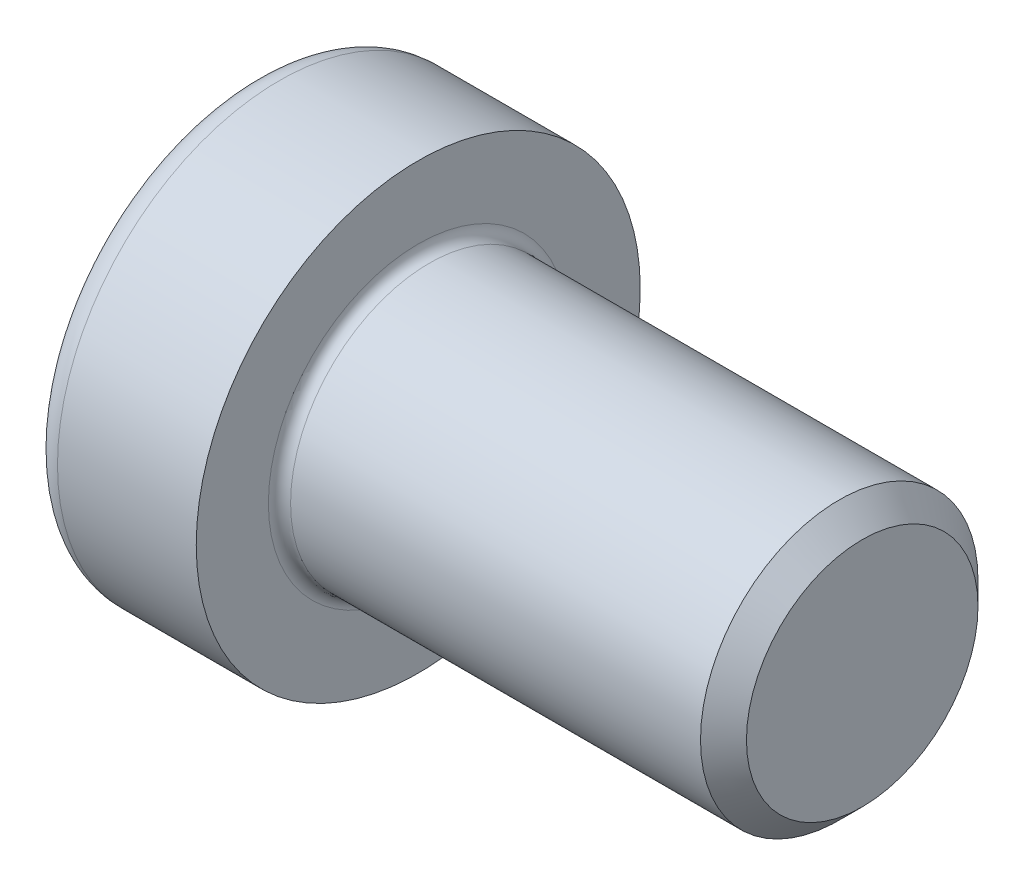
SolidWorks part; units mm, degrees
revolve "Base-Revolve" add sketch "BodySke"
sketch "BodySke" plane through (0, 0, 0) normal (0, 0, 1) x (1, 0, 0)
  line L0 (0, 0) -> (0, 8)
  line L1 (0, 8) -> (6, 8)
  line L2 (6, 8) -> (6, 5)
  line L3 (6, 5) -> (21.172, 5)
  line L4 (22, 4.172) -> (22, 0)
  line L5 (22, 0) -> (0, 0)
  line L6 (-31.75, 0) -> (127, 0) construction
  line L8 (22, 4.172) -> (21.172, 5)
  line L10 (22, -4.172) -> (21.172, -5) construction
  line L11 (7.5, 4.525) -> (7.5, -1.825) construction
  line L12 (10.5, 4.525) -> (10.5, -1.825) construction
  line L13 (-38, 4.525) -> (-38, -1.825) construction
  dimension "Head_ht" = 6
  dimension "Length" = 16
  dimension "Body_ch_ang" = 45
  dimension "Diameter" = 10
  dimension "Minor_dia" = 8.344
  dimension "Advance" = 1.5
  dimension "Thread_nom" = 11.5
  dimension "Thread_length" = 60
  dimension "Head_dia" = 16
cosmetic thread "ThreadCosmetic"
fillet "Fillet1" radius 0.4 1 edges at (6, 0, 5)
fillet "Fillet2" radius 1 1 edges at (0, 0, 8)
material "AISI 316 Нержавеющая сталь, лист (SS)"
ref_plane "Plane1" through (0, 0, 0) normal (0, 0, 1) x (1, 0, 0)
ref_plane "Plane2" through (0, 0, 0) normal (0, 1, 0) x (1, 0, 0)
ref_plane "Plane3" through (0, 0, 0) normal (1, 0, 0) x (0, 0, -1)
other "Configuration Table"
sketch "Sketch2" plane through (0, 0, 0) normal (0, 0, 1) x (1, 0, 0)
  line L0 (0, 3.5) -> (4.5, 3.5)
  line L1 (4.5, 3.5) -> (6.5207, 0)
  line L2 (-31.75, 0) -> (127, 0) construction
  line L3 (6.5207, 0) -> (0, 0)
  line L4 (0, 0) -> (0, 3.5)
  line L6 (0, 0) -> (47.625, 0) construction
  dimension "D1" = 3.5
  dimension "D2" = 60
  dimension "Depth" = 4.5
revolve "Hex-PreBroach" cut sketch "Sketch2" angle 360 about L6
sketch "Sketch3" plane through (0, 0, 0) normal (-1, 0, 0) x (0, 0.5, 0.866)
  line L0 (2.0207, 3.5) -> (-2.0207, 3.5)
  line L1 (-2.0207, 3.5) -> (-4.0415, 0)
  line L2 (2.0207, 3.5) -> (4.0415, 0)
  line L3 (2.0207, -3.5) -> (4.0415, 0)
  line L4 (2.0207, -3.5) -> (-2.0207, -3.5)
  line L5 (-2.0207, -3.5) -> (-4.0415, 0)
  dimension "D1" = 3.5
  dimension "D2" = 3.5
  dimension "Hex_size" = 7
extrude "Hex" cut sketch "Sketch3" against normal blind 4.5
sketch "ThdSchSke" plane through (0, 0, 0) normal (0, 0, 1) x (1, 0, 0)
  line L0 (10.5, -4.172) -> (9.9202, -5)
  line L1 (10.5, -4.172) -> (11.0798, -5)
  line L2 (11.0798, -5) -> (11.0798, -6.25)
  line L3 (-3.175, 0) -> (5.1513, 0) construction
  line L4 (0, 7) -> (0, -7) construction
  line L5 (11.0798, -6.25) -> (9.9202, -6.25)
  line L6 (9.9202, -6.25) -> (9.9202, -5)
  dimension "Thread_minor" = 8.344
  dimension "Diameter" = 10
  dimension "Start" = 10.5
revolve "ThreadSchematic" [suppressed] cut sketch "ThdSchSke" angle 360 about L3
pattern_linear "ThdSchPat" [suppressed]
equation "\"D2@Sketch3\" = \"Hex_size@Sketch3\" / 2"
equation "\"D1@Sketch3\" = \"Hex_size@Sketch3\" / 2"
equation "\"D1@Sketch2\" = \"Hex_size@Sketch3\" / 2"
equation "\"Thread_minor@ThreadCosmetic\"  =  \"Minor_dia@BodySke\""
equation "\"Depth@Sketch2\" =  \"Key_eng@Hex\""
equation "\"Thread_length@ThreadCosmetic\" = ((sgn( (\"Length@BodySke\" - \"Advance@BodySke\" * 3.0) - \"Thread_nom@BodySke\" )-1)*( (\"Length@BodySke\" - \"Advance@BodySke\" * 3.0) - \"Thread_nom@BodySke\" ))/-2+ \"Thread_nom@BodySke\""
equation "\"Thread_minor@ThdSchSke\" = \"Minor_dia@BodySke\""
equation "\"Diameter@ThdSchSke\" = \"Diameter@BodySke\""
equation "\"Overcut@ThdSchSke\" = \"Diameter@BodySke\" * 1.25"
equation "\"Start@ThdSchSke\" = \"Head_ht@BodySke\" + \"Length@BodySke\" - \"Thread_length@ThreadCosmetic\"  '---Non-countersunk---"
equation "\"Num_threads@ThdSchPat\" = int( \"Thread_length@ThreadCosmetic\" / \"Advance@BodySke\" + 0.999 )  + 1"
equation "\"Advance@ThdSchPat\" = \"Thread_length@ThreadCosmetic\" /  (\"Num_threads@ThdSchPat\" - 1) 'relax it"
equation "\"Num_threads@ThdSchPat\" = \"Num_threads@ThdSchPat\" - sgn( \"Num_threads@ThdSchPat\" - 1) '---chamfered tips only---"
